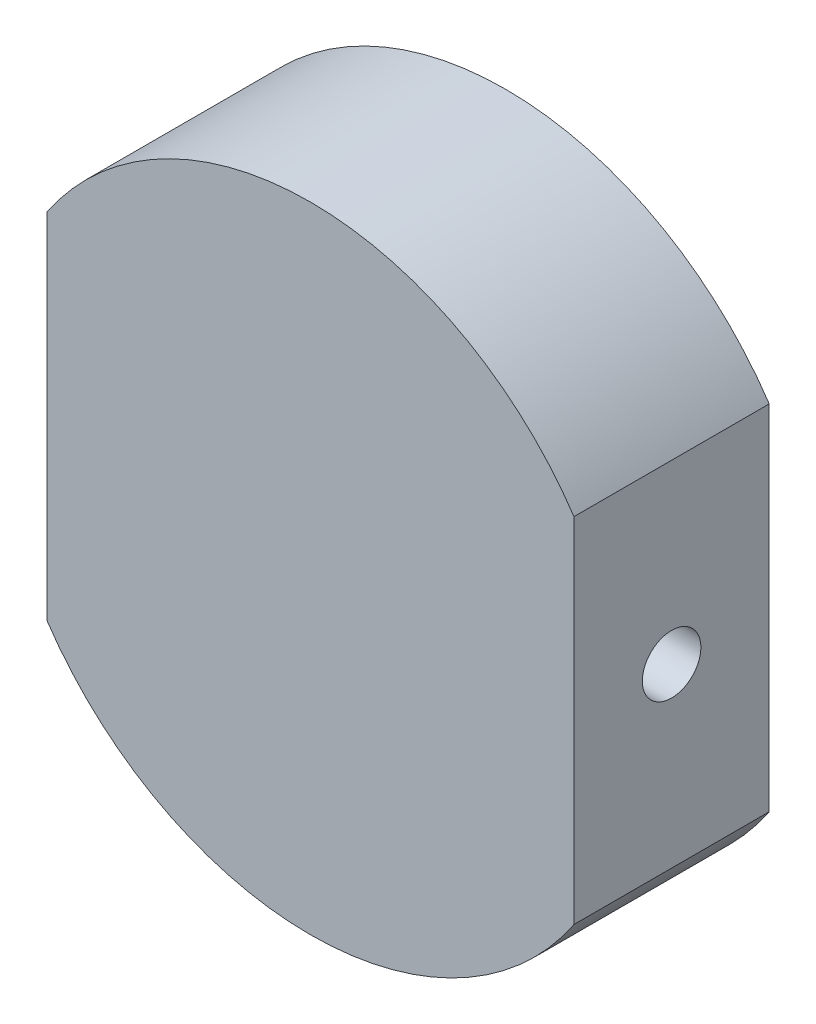
SolidWorks part; units mm, degrees
ref_plane "Спереди" through (0, 0, 0) normal (0, 0, 1) x (1, 0, 0)
ref_plane "Сверху" through (0, 0, 0) normal (0, 1, 0) x (1, 0, 0)
ref_plane "Справа" through (0, 0, 0) normal (1, 0, 0) x (0, 0, -1)
sketch "Эскиз3" plane through (0, 0, 0) normal (0, 0, 1) x (1, 0, 0)
  circle A0 centre (0, 0) radius 32.5
  dimension "D1" = 65
extrude "Вытянуть3" add sketch "Эскиз3" along normal blind 20
sketch "Эскиз4" plane through (0, 0, 0) normal (0, 1, 0) x (1, 0, 0)
  line L0 (0, 0) -> (0, 23.4902) construction
  line L1 (-27, 17.621) -> (-27, -27.5269)
  line L2 (27, 17.621) -> (27, -27.5269)
  line L3 (-27, 17.621) -> (-44.8899, 17.621)
  line L4 (-44.8899, 17.621) -> (-44.8899, -27.5269)
  line L5 (-44.8899, -27.5269) -> (-27, -27.5269)
  line L6 (27, -27.5269) -> (44.9545, -27.5269)
  line L7 (44.9545, -27.5269) -> (44.9545, 17.621)
  line L8 (44.9545, 17.621) -> (27, 17.621)
  dimension "D1" = 27
  dimension "D2" = 27
  dimension "D3" = 44.9545
  dimension "D4" = 44.8899
  dimension "D5" = 17.621
  dimension "D6" = 17.621
  dimension "D7" = 27.5269
  dimension "D8" = 27.5269
extrude "Вырез-Вытянуть1" cut sketch "Эскиз4" against normal mid plane 80
sketch "Эскиз5" plane through (27, 0, 0) normal (1, 0, 0) x (0, 0, -1)
  line L0 (0, 0) -> (23.8106, 0) construction
  line L2 (-20, 32.5) -> (-20, 39.8726) construction
  line L3 (0, 32.5) -> (0, 38.7908) construction
  line L4 (-10, 39.9558) -> (-10, 35.9618) construction
  line L5 (0, 18.0901) -> (0, -18.0901) construction
  line L6 (-20, 18.0901) -> (0, 18.0901) construction
  circle A0 centre (-10, 0) radius 3
extrude "Вырез-Вытянуть2" cut sketch "Эскиз5" against normal blind 60
